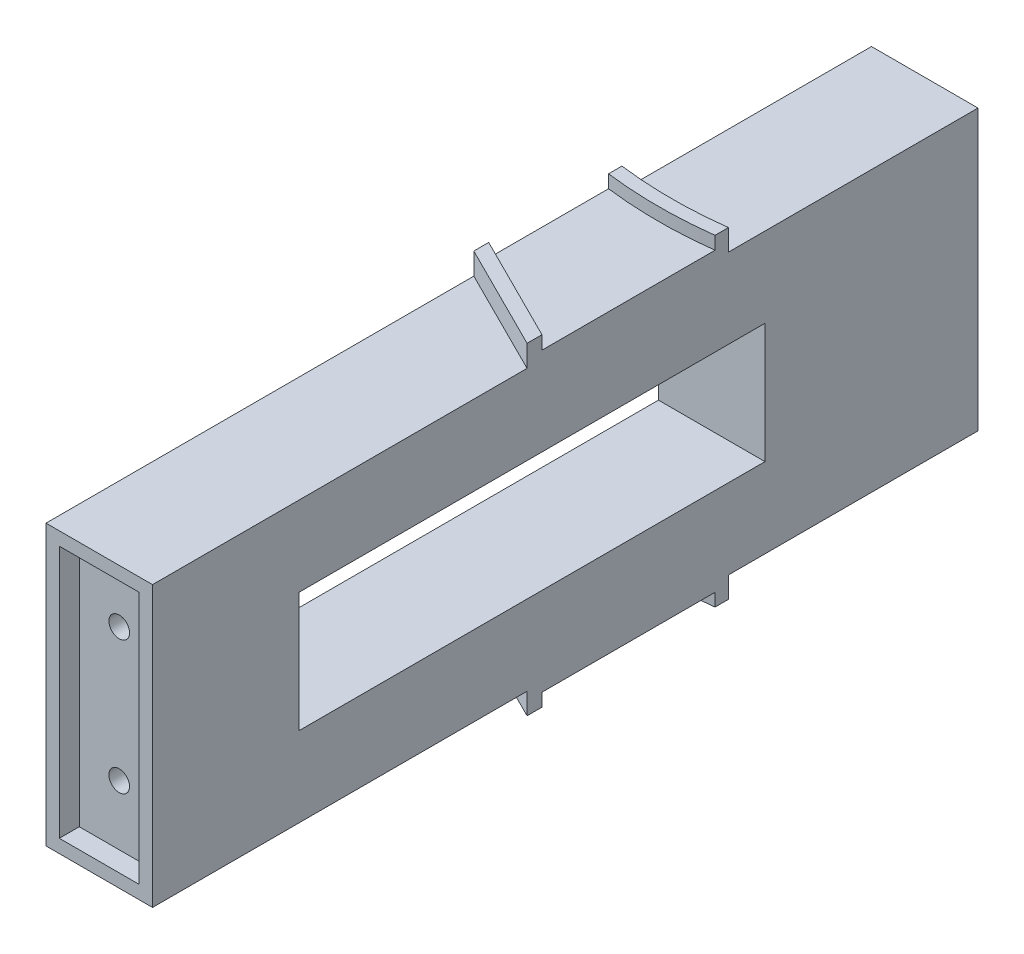
SolidWorks part; units mm, degrees
ref_plane "Спереди" through (0, 0, 0) normal (0, 0, 1) x (1, 0, 0)
ref_plane "Сверху" through (0, 0, 0) normal (0, 1, 0) x (1, 0, 0)
ref_plane "Справа" through (0, 0, 0) normal (1, 0, 0) x (0, 0, -1)
sketch "Эскиз1" plane through (0, 0, 0) normal (0, 0, 1) x (1, 0, 0)
  line L1 (8, -21) -> (-8, -21)
  line L2 (8, -21) -> (8, 21)
  line L3 (8, 21) -> (-8, 21)
  line L4 (-8, -21) -> (-8, 21)
  line L5 (8, -21) -> (-8, 21) construction
  line L6 (8, 21) -> (-8, -21) construction
  point P0 (0, 0)
  dimension "D1" = 16
  dimension "D2" = 42
extrude "Бобышка-Вытянуть1" add sketch "Эскиз1" along normal blind 124
sketch "Эскиз5" plane through (0, 0, 0) normal (0, 1, 0) x (1, 0, 0)
  line L0 (-8, -37.4859) -> (-8, -39.502)
  line L2 (8, -39.502) -> (8, -37.4859)
  arc A0 (-8, -37.4859) -> (8, -37.4859) centre (0, 24.5) ccw
  arc A1 (-8, -39.502) -> (8, -39.502) centre (0, 24.5) ccw
  circle A3 centre (0, 24.5) radius 64.5 construction
  circle A4 centre (0, 24.5) radius 62.5 construction
  point P0 (0, -38)
  point P3 (0, -40)
  point P4 (0, -38)
  point P6 (59.769, 42.7732)
  point P15 (64.5, 24.5)
  point P17 (0, 24.5)
  point P19 (-8, -49.2379)
  point P20 (0, 0)
  point P21 (-8, -37.4859)
  point P22 (-8, -39.502)
  dimension "D2" = 125
  dimension "D3" = 0
  dimension "D4" = 2
extrude "Бобышка-Вытянуть4" add sketch "Эскиз5" along normal blind 24.1932 and the other way blind 24.175
sketch "Эскиз6" plane through (0, 0, 0) normal (0, 1, 0) x (1, 0, 0)
  line L0 (-8, -124) -> (-8, -39.502) construction
  line L1 (8, -124) -> (8, -39.502) construction
  line L2 (-8, -57.5) -> (8, -65.5)
  line L3 (8, -65.5) -> (8, -67.7361)
  line L4 (-8, -59.7361) -> (8, -67.7361)
  line L5 (-8, -57.5) -> (-8, -59.7361)
  arc A0 (-8, -39.502) -> (8, -39.502) centre (0, 24.5) ccw construction
  point P0 (0, -40)
  point P1 (-8, -57.5)
  point P5 (8, -65.5)
  dimension "D1" = 17.5
  dimension "D2" = 25.5
extrude "Бобышка-Вытянуть5" add sketch "Эскиз6" along normal blind 24.2632 and the other way blind 24.198
sketch "Эскиз7" plane through (0, 0, 124) normal (0, 0, 1) x (1, 0, 0)
  line L0 (-6, -19) -> (-6, 19)
  line L5 (6, 19) -> (-6, 19)
  line L6 (6, -19) -> (6, 19)
  line L7 (6, -19) -> (-6, -19)
  point P0 (0, 0)
extrude "Вырез-Вытянуть1" cut sketch "Эскиз7" against normal blind 3
sketch "Эскиз8" plane through (0, 0, 0) normal (0, 0, -1) x (-1, 0, 0)
  line L0 (-6, -19) -> (-6, 19)
  line L5 (6, 19) -> (-6, 19)
  line L6 (6, -19) -> (6, 19)
  line L7 (6, -19) -> (-6, -19)
extrude "Вырез-Вытянуть2" cut sketch "Эскиз8" against normal blind 25
sketch "Эскиз9" plane through (-8, 0, 0) normal (-1, 0, 0) x (0, 0, 1)
  line L1 (21, -10) -> (25, -10)
  line L2 (21, -10) -> (21, 10)
  line L3 (21, 10) -> (25, 10)
  line L4 (25, -10) -> (25, 10)
  line L5 (21, -10) -> (25, 10) construction
  line L6 (21, 10) -> (25, -10) construction
  point P0 (25, 0)
  point P1 (23, 0)
  point P3 (23, 0)
  dimension "D1" = 25
  dimension "D2" = 2
  dimension "D3" = 20
  dimension "D4" = 0
extrude "Вырез-Вытянуть3" cut sketch "Эскиз9" against normal blind 2
sketch "Эскиз10" plane through (0, 0, 121) normal (0, 0, 1) x (1, 0, 0)
  circle A0 centre (0, 10) radius 1.55
  circle A1 centre (0, -10) radius 1.55
  point P0 (0, 10)
  point P1 (0, -10)
  dimension "D3" = 3.1
  dimension "D4" = 3.1
  dimension "D1" = 10
  dimension "D2" = 10
extrude "Вырез-Вытянуть4" cut sketch "Эскиз10" against normal blind 20
sketch "Эскиз12" plane through (0, 0, 0) normal (0, 1, 0) x (1, 0, 0)
  line L0 (-8, -57.5) -> (8, -65.5)
  line L1 (-8, -39.502) -> (-8, -57.5)
  line L2 (8, -65.5) -> (8, -39.502) construction
  line L4 (8, -47.502) -> (8, -65.5)
  line L5 (-8, -39.502) -> (8, -39.502)
  line L6 (8, -39.502) -> (8, -47.502)
  point P0 (-8, -57.5)
  point P1 (8, -65.5)
  point P6 (-8, -39.502)
  point P9 (8, -47.502)
  dimension "D1" = 17.998
extrude "Бобышка-Вытянуть10" add sketch "Эскиз12" along normal blind 22.25 and the other way blind 22.25
sketch "Эскиз13" plane through (-8, 0, 0) normal (-1, 0, 0) x (0, 0, 1)
  line L0 (124, 21) -> (124, -21) construction
  line L1 (25, 19) -> (25, -19) construction
  line L2 (37.4859, -21) -> (0, -21) construction
  line L3 (32, 9) -> (102, 9)
  line L4 (32, 9) -> (32, -9)
  line L5 (32, -9) -> (102, -9)
  line L6 (102, 9) -> (102, -9)
  line L7 (37.4859, 21) -> (0, 21) construction
  point P0 (72.6003, 0)
  point P1 (32, 0)
  point P2 (124, 0)
  point P5 (102, 0)
  point P6 (124, 0)
  point P7 (25, 0)
  dimension "D1" = 7
  dimension "D2" = 22
  dimension "D3" = 12
  dimension "D5" = 12
extrude "Вырез-Вытянуть5" cut sketch "Эскиз13" against normal blind 22.25
